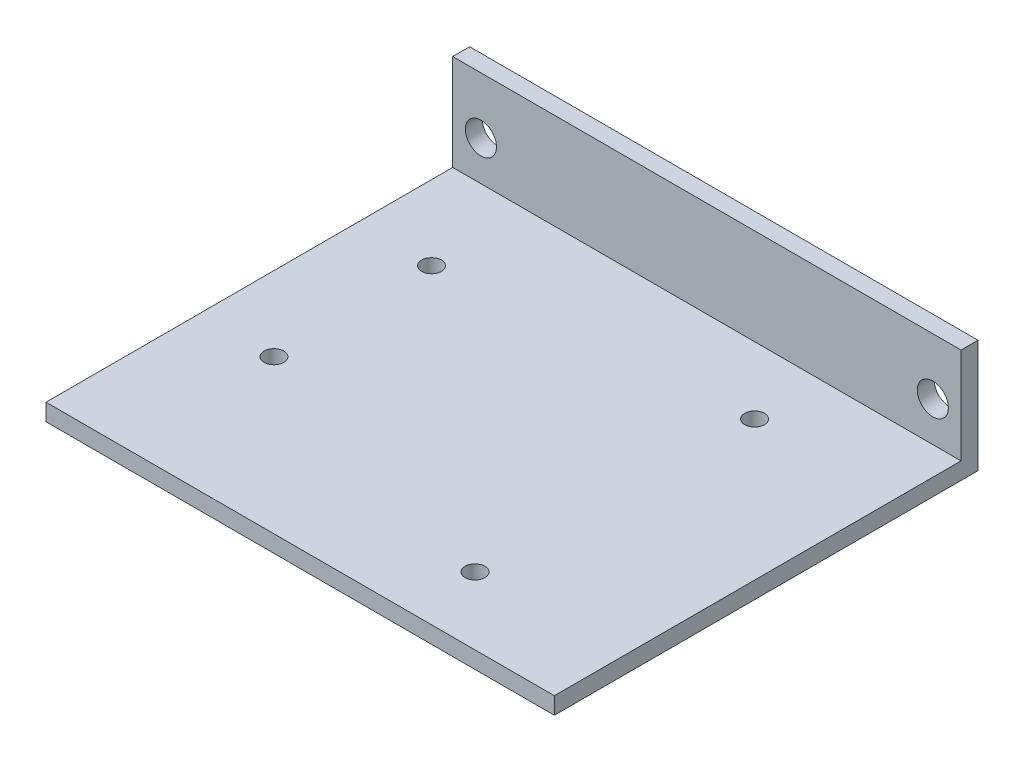
SolidWorks part; units mm, degrees
ref_plane "Front Plane" through (0, 0, 0) normal (0, 0, 1) x (1, 0, 0)
ref_plane "Top Plane" through (0, 0, 0) normal (0, 1, 0) x (1, 0, 0)
ref_plane "Right Plane" through (0, 0, 0) normal (1, 0, 0) x (0, 0, -1)
sketch "Sketch1" plane through (0, 0, 0) normal (0, 1, 0) x (1, 0, 0)
  line L1 (-45, 37.5) -> (45, 37.5)
  line L2 (-45, 37.5) -> (-45, -37.5)
  line L3 (-45, -37.5) -> (45, -37.5)
  line L4 (45, 37.5) -> (45, -37.5)
  line L5 (-45, 37.5) -> (45, -37.5) construction
  line L6 (-45, -37.5) -> (45, 37.5) construction
  point P0 (0, 0)
  dimension "D1" = 90
  dimension "D2" = 75
extrude "Boss-Extrude1" add sketch "Sketch1" along normal blind 3
sketch "Sketch2" plane through (0, 3, 0) normal (0, 1, 0) x (1, 0, 0)
  line L0 (45, -37.5) -> (45, 37.5) construction
  line L1 (-45, 37.5) -> (45, 37.5)
  line L2 (-45, 37.5) -> (-45, 34.5)
  line L3 (-45, 34.5) -> (45, 34.5)
  line L4 (45, 37.5) -> (45, 34.5)
  dimension "D1" = 3
extrude "Boss-Extrude2" add sketch "Sketch2" along normal offset from surface (17 mm away) 20 up to face at (0, 0, 0)
sketch "Sketch3" plane through (0, 0, -37.5) normal (0, 0, -1) x (-1, 0, 0)
  line L0 (0, 20) -> (0, 0) construction
  line L1 (-45, 20) -> (45, 20) construction
  line L2 (-40, 10) -> (40, 10) construction
  line L3 (45, 20) -> (45, 0) construction
  point P8 (0, 10)
  dimension "D1" = 5
hole_wizard "M5 Clearance Hole1" positions "3DSketch1" profile "Sketch4" hole size "M5" standard "ANSI Metric" end condition through all
sketch3d "3DSketch1"
  point P0 (40, 10, -37.5)
  point P3 (-40, 10, -37.5)
sketch "Sketch4" plane through (40, 10, -37.5) normal (1, 0, 0) x (0, 1, 0)
  line L0 (0, 0) -> (0, 75)
  line L1 (0, 75) -> (2.75, 75)
  line L2 (2.75, 75) -> (2.75, 0)
  line L5 (2.75, 0) -> (0, 0)
  line L11 (0, -6.35) -> (0, 107.95) construction
  dimension "Thru Hole Dia." = 5.5
  dimension "Thru Hole Depth" = 75
sketch "Sketch5" plane through (0, 3, 0) normal (0, 1, 0) x (1, 0, 0)
  line L0 (0, 34.5) -> (0, -37.5) construction
  line L1 (-45, 34.5) -> (45, 34.5) construction
  line L2 (-45, -37.5) -> (45, -37.5) construction
  line L3 (-31.8, -10.35) -> (-31.8, 17.55) construction
  line L4 (-34.3, 25.15) -> (34.3, 25.15) construction
  line L5 (-34.3, 25.15) -> (-34.3, -28.15) construction
  line L6 (-34.3, -28.15) -> (34.3, -28.15) construction
  line L7 (34.3, 25.15) -> (34.3, -28.15) construction
  line L8 (-34.3, 25.15) -> (34.3, -28.15) construction
  line L9 (-34.3, -28.15) -> (34.3, 25.15) construction
  circle A0 centre (-31.8, 17.55) radius 1.75
  circle A1 centre (-31.8, -10.35) radius 1.75
  circle A2 centre (19, -25.55) radius 1.75
  circle A4 centre (20.3, 22.65) radius 1.75
  point P6 (0, -1.5)
  point P11 (-31.8, 17.55)
  point P12 (-31.8, -10.35)
  point P15 (20.3, 22.65)
  point P16 (19, -25.55)
  dimension "D10" = 3.5
  dimension "D1" = 68.6
  dimension "D2" = 53.3
  dimension "D3" = 2.5
  dimension "D4" = 5.1
  dimension "D5" = 27.9
  dimension "D6" = 15.2
  dimension "D7" = 1.3
  dimension "D8" = 14
  dimension "D9" = 50.8
extrude "Cut-Extrude1" cut sketch "Sketch5" against normal up to next
